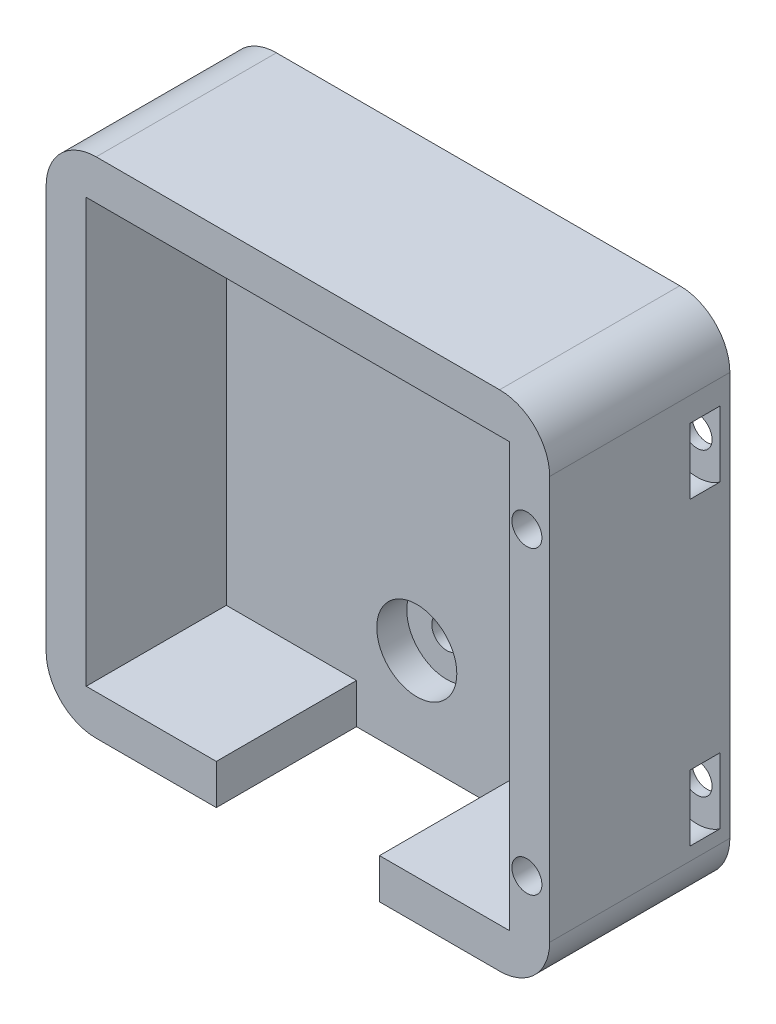
SolidWorks part; units mm, degrees
ref_plane "Front" through (0, 0, 0) normal (0, 0, 1) x (1, 0, 0)
ref_plane "Top" through (0, 0, 0) normal (0, 1, 0) x (1, 0, 0)
ref_plane "Right" through (0, 0, 0) normal (1, 0, 0) x (0, 0, -1)
sketch "Esquisse1" plane through (0, 0, 0) normal (0, 0, 1) x (1, 0, 0)
  line L1 (0, 0) -> (50.3, 0)
  line L2 (0, 0) -> (0, 50.3)
  line L3 (0, 50.3) -> (50.3, 50.3)
  line L4 (50.3, 0) -> (50.3, 50.3)
  dimension "D1" = 50.3
  dimension "D2" = 50.3
extrude "Boss.-Extru.1" add sketch "Esquisse1" along normal blind 4
sketch "Esquisse2" plane through (0, 0, 4) normal (0, 0, 1) x (1, 0, 0)
  line L0 (50.3, 50.3) -> (0, 50.3) construction
  line L1 (4, 46.3) -> (46.3, 46.3)
  line L2 (4, 46.3) -> (4, 4)
  line L3 (4, 4) -> (17, 4)
  line L4 (46.3, 46.3) -> (46.3, 4)
  line L5 (0, 0) -> (50.3, 0) construction
  line L6 (0, 50.3) -> (0, 0) construction
  line L7 (50.3, 0) -> (50.3, 50.3) construction
  line L8 (33.3, 4) -> (46.3, 4)
  line L9 (33.3, 0) -> (50.3, 0)
  line L10 (17, 4) -> (17, 0)
  line L11 (0, 50.3) -> (50.3, 50.3)
  line L12 (33.3, 4) -> (33.3, 0)
  line L13 (0, 50.3) -> (0, 0)
  line L14 (0, 0) -> (17, 0)
  line L15 (50.3, 50.3) -> (50.3, 0)
  point P16 (17, 2)
  point P17 (33.3, 2)
  dimension "D1" = 4
  dimension "D2" = 4
  dimension "D3" = 4
  dimension "D4" = 4
  dimension "D5" = 16.3
  dimension "D6" = 13
extrude "Boss.-Extru.2" add sketch "Esquisse2" along normal blind 14
sketch "Esquisse3" plane through (0, 0, 0) normal (0, 0, -1) x (-1, 0, 0)
  circle A0 centre (-23.0242, 39.6) radius 1.5
  circle A1 centre (-48.0242, 39.6) radius 1.5
  circle A2 centre (-48.0242, 9.6) radius 1.5
  circle A3 centre (-23.0242, 9.6) radius 1.5
  dimension "D1" = 3
  dimension "D2" = 3
  dimension "D3" = 3
  dimension "D4" = 3
extrude "Enlèv. mat.-Extru.1" cut sketch "Esquisse3" against normal through all
fillet "Congé2" radius 5 1 edges at (0, 50.3, 9)
sketch "Esquisse4" plane through (0, 0, 4) normal (0, 0, 1) x (1, 0, 0)
  circle A0 centre (23.0242, 39.6) radius 4
  circle A1 centre (23.0242, 9.6) radius 4
  circle A2 centre (48.0242, 39.6) radius 4
  circle A3 centre (48.0242, 9.6) radius 4
  dimension "D1" = 8
  dimension "D2" = 8
  dimension "D3" = 8
  dimension "D4" = 8
extrude "Enlèv. mat.-Extru.2" cut sketch "Esquisse4" against normal blind 3
fillet "Congé6" radius 5 3 edges at (50.3, 50.3, 9) (0, 0, 9) (50.3, 0, 9)
